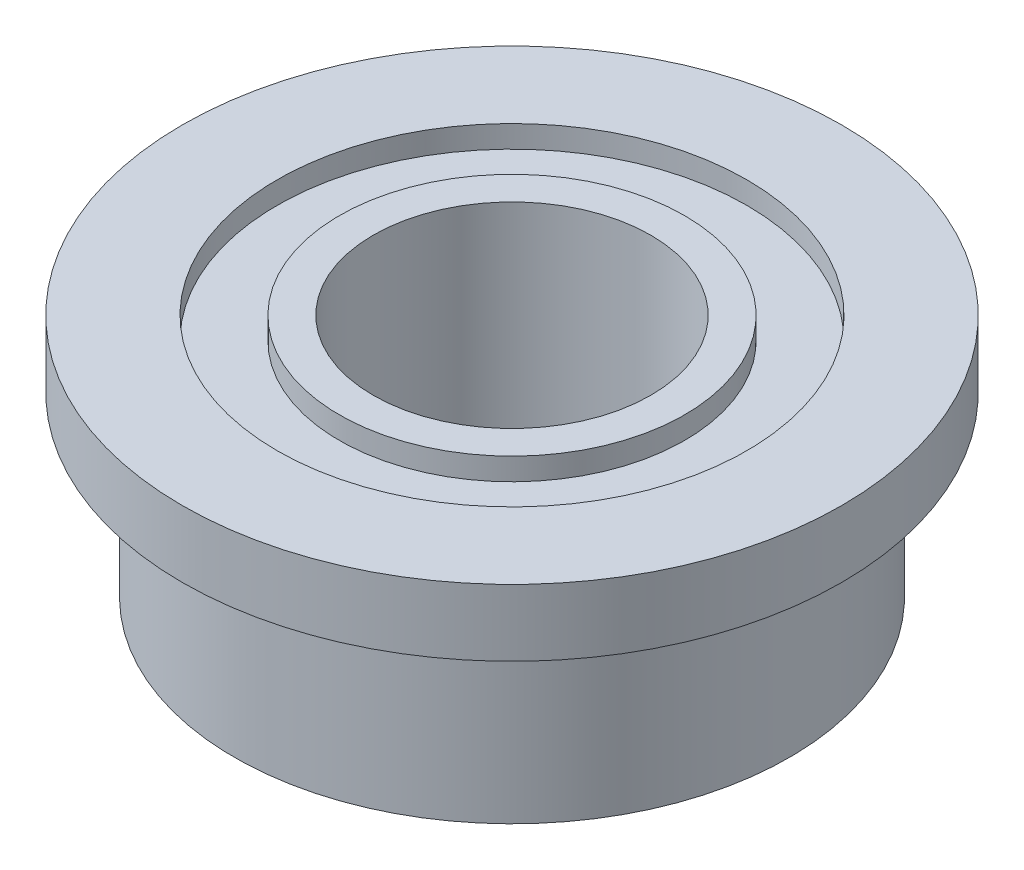
SolidWorks part; units mm, degrees
material "Chrome Stainless Steel"
ref_plane "Front Plane" through (0, 0, 0) normal (0, 0, 1) x (1, 0, 0)
ref_plane "Top Plane" through (0, 0, 0) normal (0, 1, 0) x (1, 0, 0)
ref_plane "Right Plane" through (0, 0, 0) normal (1, 0, 0) x (0, 0, -1)
sketch "Sketch1" plane through (0, 0, 0) normal (0, 0, 1) x (1, 0, 0)
  line L0 (1.9748, 0.254) -> (2.686, 0.254)
  line L1 (2.686, 0.254) -> (2.686, 0)
  line L2 (2.686, 0) -> (3.175, 0)
  line L3 (3.175, 0) -> (3.175, 1.7272)
  line L4 (3.175, 1.7272) -> (3.0734, 1.7272)
  line L5 (3.0734, 1.7272) -> (3.0734, 2.032)
  line L6 (3.0734, 2.032) -> (3.7719, 2.032)
  line L7 (3.7719, 2.032) -> (3.7719, 2.794)
  line L8 (3.7719, 2.794) -> (2.686, 2.794)
  line L9 (2.686, 2.794) -> (2.686, 2.54)
  line L10 (2.686, 2.54) -> (1.9748, 2.54)
  line L11 (1.9748, 2.54) -> (1.9748, 2.794)
  line L12 (1.9748, 2.794) -> (1.5875, 2.794)
  line L13 (1.5875, 2.794) -> (1.5875, 0)
  line L14 (1.5875, 0) -> (1.9748, 0)
  line L15 (1.9748, 0) -> (1.9748, 0.254)
  line L16 (0, 2.794) -> (0, 0) construction
revolve "Revolve1" add sketch "Sketch1" angle 360 about L16
